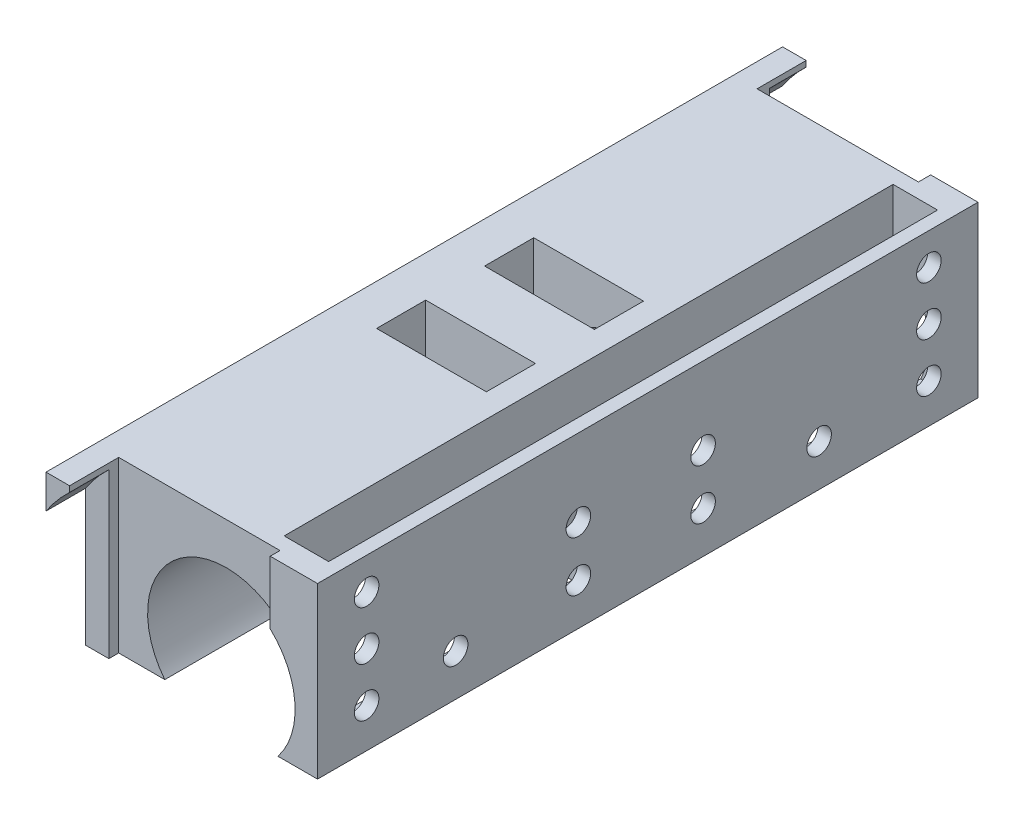
SolidWorks part; units mm, degrees
ref_plane "Plan de face" through (0, 0, 0) normal (0, 0, 1) x (1, 0, 0)
ref_plane "Plan de dessus" through (0, 0, 0) normal (0, 1, 0) x (1, 0, 0)
ref_plane "Plan de droite" through (0, 0, 0) normal (1, 0, 0) x (0, 0, -1)
sketch "Cube" plane through (0, 0, 0) normal (0, 1, 0) x (1, 0, 0)
  line L1 (-109.2105, 63.4868) -> (40.7895, 63.4868)
  line L2 (-109.2105, 63.4868) -> (-109.2105, -86.5132)
  line L3 (-109.2105, -86.5132) -> (40.7895, -86.5132)
  line L4 (40.7895, 63.4868) -> (40.7895, -86.5132)
  dimension "D1" = 150
  dimension "D2" = 150
extrude "Boss.-Extru.1" add sketch "Cube" along normal blind 34.5
sketch "Pave" plane through (0, 34.5, 0) normal (0, 1, 0) x (1, 0, 0)
  line L0 (40.7895, -86.5132) -> (40.7895, 63.4868) construction
  line L1 (-109.2105, -86.5132) -> (40.7895, -86.5132) construction
  line L2 (40.7895, 63.4868) -> (-109.2105, 63.4868) construction
  line L4 (37.7895, -83.5132) -> (-58.2105, -83.5132)
  line L5 (37.7895, -83.5132) -> (37.7895, 60.4868)
  line L6 (37.7895, 60.4868) -> (-58.2105, 60.4868)
  line L7 (-58.2105, -83.5132) -> (-58.2105, 60.4868)
  point P0 (37.7895, -83.5132)
  point P5 (-58.2105, 60.4868)
  dimension "D1" = 3
  dimension "D2" = 3
  dimension "D3" = 3
  dimension "D4" = 99
extrude "Enlèv. mat.-Extru.1" cut sketch "Pave" against normal blind 31.5
sketch "Vis1" plane through (0, 0, 86.5132) normal (0, 0, 1) x (1, 0, 0)
  line L0 (40.7895, 34.5) -> (40.7895, 0) construction
  line L1 (-109.2105, 0) -> (40.7895, 0) construction
  circle A0 centre (33.7895, 10) radius 2.5
  circle A1 centre (33.7895, 20) radius 2.5
  circle A2 centre (33.7895, 30) radius 2.5
  point P0 (33.7895, 10)
  point P3 (33.7895, 20)
  point P4 (33.7895, 30)
  dimension "D1" = 7
  dimension "D2" = 7
  dimension "D3" = 7
  dimension "D4" = 10
  dimension "D5" = 20
  dimension "D6" = 30
extrude "Enlèv. mat.-Extru.2" cut sketch "Vis1" against normal blind 5
sketch "Vis2" plane through (0, 0, -63.4868) normal (0, 0, -1) x (-1, 0, 0)
  line L0 (-40.7895, 34.5) -> (-40.7895, 0) construction
  line L1 (-40.7895, 0) -> (109.2105, 0) construction
  circle A0 centre (-33.7895, 10) radius 2.5
  circle A1 centre (-33.7895, 20) radius 2.5
  circle A2 centre (-33.7895, 30) radius 2.5
  point P0 (-33.7895, 10)
  point P1 (-33.7895, 20)
  point P2 (-33.7895, 30)
  dimension "D1" = 7
  dimension "D2" = 7
  dimension "D3" = 7
  dimension "D4" = 10
  dimension "D5" = 20
  dimension "D6" = 30
extrude "Enlèv. mat.-Extru.3" cut sketch "Vis2" against normal blind 5
sketch "Pave proche moteur" plane through (0, 34.5, 0) normal (0, 1, 0) x (1, 0, 0)
  line L0 (-109.2105, -86.5132) -> (40.7895, -86.5132) construction
  line L1 (-58.2105, 60.4868) -> (-58.2105, -83.5132) construction
  line L2 (40.7895, 63.4868) -> (-109.2105, 63.4868) construction
  line L4 (-61.2105, 50.4868) -> (-73.7105, 50.4868)
  line L5 (-61.2105, 50.4868) -> (-61.2105, -73.5132)
  line L6 (-61.2105, -73.5132) -> (-73.7105, -73.5132)
  line L7 (-73.7105, 50.4868) -> (-73.7105, -73.5132)
  point P0 (-61.2105, -73.5132)
  point P5 (-61.2105, 50.4868)
  dimension "D1" = 13
  dimension "D2" = 3
  dimension "D3" = 13
  dimension "D4" = 3
  dimension "D5" = 12.5
extrude "Enlèv. mat.-Extru.4" cut sketch "Pave proche moteur" against normal blind 31.5
sketch "Pave Roue libre" plane through (0, 34.5, 0) normal (0, 1, 0) x (1, 0, 0)
  line L0 (40.7895, 63.4868) -> (-109.2105, 63.4868) construction
  line L1 (-58.2105, 60.4868) -> (-58.2105, -83.5132) construction
  line L2 (-109.2105, -86.5132) -> (40.7895, -86.5132) construction
  line L3 (-71.5505, 53.4868) -> (-104.4105, 53.4868)
  line L4 (-71.5505, 53.4868) -> (-71.5505, 69.1835)
  line L5 (-71.5505, 69.1835) -> (-104.4105, 69.1835)
  line L6 (-104.4105, 53.4868) -> (-104.4105, 69.1835)
  line L8 (-71.5505, -76.5132) -> (-104.4105, -76.5132)
  line L9 (-71.5505, -76.5132) -> (-71.5505, -94.9327)
  line L10 (-71.5505, -94.9327) -> (-104.4105, -94.9327)
  line L11 (-104.4105, -76.5132) -> (-104.4105, -94.9327)
  point P0 (-71.5505, 53.4868)
  point P9 (-71.5505, -76.5132)
  dimension "D1" = 10
  dimension "D2" = 13.34
  dimension "D3" = 32.86
  dimension "D4" = 13.34
  dimension "D5" = 10
extrude "Enlèv. mat.-Extru.5" cut sketch "Pave Roue libre" against normal blind 36
sketch "Cables" plane through (0, 34.5, 0) normal (0, 1, 0) x (1, 0, 0)
  line L0 (40.7895, 63.4868) -> (-71.5505, 63.4868) construction
  line L1 (-58.2105, 60.4868) -> (-58.2105, -83.5132) construction
  line L2 (-71.5505, -86.5132) -> (40.7895, -86.5132) construction
  line L3 (-58.2105, 60.4868) -> (-58.2105, -83.5132) construction
  line L5 (-100.8905, -5.5132) -> (-78.5305, -5.5132)
  line L6 (-100.8905, -5.5132) -> (-100.8905, 4.4868)
  line L7 (-100.8905, 4.4868) -> (-78.5305, 4.4868)
  line L8 (-78.5305, -5.5132) -> (-78.5305, 4.4868)
  line L9 (-100.8905, -17.5132) -> (-78.5305, -17.5132)
  line L10 (-100.8905, -17.5132) -> (-100.8905, -27.5132)
  line L11 (-100.8905, -27.5132) -> (-78.5305, -27.5132)
  line L12 (-78.5305, -17.5132) -> (-78.5305, -27.5132)
  point P0 (-100.8905, -5.5132)
  point P5 (-100.8905, -17.5132)
  dimension "D1" = 69
  dimension "D2" = 42.68
  dimension "D3" = 69
  dimension "D4" = 42.68
  dimension "D5" = 22.36
  dimension "D6" = 10
  dimension "D7" = 22.36
  dimension "D8" = 10
extrude "Enlèv. mat.-Extru.6" cut sketch "Cables" against normal blind 36
sketch "Roue ext" plane through (0, 0, 86.5132) normal (0, 0, 1) x (1, 0, 0)
  circle A0 centre (-82.5, 10) radius 32
  point P0 (-82.5, 10)
extrude "Enlèv. mat.-Extru.7" cut sketch "Roue ext" against normal blind 8
sketch "Roue inter" plane through (0, 0, 86.5132) normal (0, 0, 1) x (1, 0, 0)
  circle A0 centre (-82.5, 10) radius 16.02
  point P0 (-82.5, 10)
extrude "Enlèv. mat.-Extru.8" cut sketch "Roue inter" against normal blind 69
sketch "Roue ext2" plane through (0, 0, -63.4868) normal (0, 0, -1) x (-1, 0, 0)
  circle A0 centre (82.5, 10) radius 32
  point P0 (82.5, 10)
extrude "Enlèv. mat.-Extru.9" cut sketch "Roue ext2" against normal blind 7.5
sketch "Roue inter2" plane through (0, 0, -63.4868) normal (0, 0, -1) x (-1, 0, 0)
  circle A0 centre (82.5, 10) radius 16.02
  point P0 (82.5, 10)
extrude "Enlèv. mat.-Extru.10" cut sketch "Roue inter2" against normal blind 69
sketch "Vis Moteur pour support" plane through (-58.2105, 0, 0) normal (1, 0, 0) x (0, 0, -1)
  line L0 (55.9868, 3) -> (-78.5132, 3) construction
  line L1 (-78.5132, 3) -> (-78.5132, 30.8332) construction
  line L2 (55.9868, 30.8332) -> (55.9868, 3) construction
  circle A0 centre (-68.5132, 8) radius 2.5
  circle A1 centre (-68.5132, 18) radius 2.5
  circle A2 centre (-68.5132, 28) radius 2.5
  circle A3 centre (45.9868, 8) radius 2.5
  circle A4 centre (45.9868, 18) radius 2.5
  circle A5 centre (45.9868, 28) radius 2.5
  point P0 (-68.5132, 8)
  point P1 (-68.5132, 18)
  point P2 (-68.5132, 28)
  point P13 (45.9868, 18)
  point P14 (45.9868, 28)
  point P15 (45.9868, 8)
  dimension "D7" = 5
  dimension "D1" = 5
  dimension "D2" = 15
  dimension "D3" = 25
  dimension "D4" = 10
  dimension "D5" = 10
  dimension "D6" = 10
  dimension "D8" = 15
  dimension "D9" = 25
  dimension "D10" = 10
  dimension "D11" = 10
  dimension "D12" = 10
extrude "Enlèv. mat.-Extru.11" cut sketch "Vis Moteur pour support" against normal blind 10
sketch "Esquisse1" plane through (0, 3, 0) normal (0, 1, 0) x (1, 0, 0)
  line L0 (-58.2105, 55.9868) -> (-58.2105, -78.5132) construction
  line L1 (37.7895, 60.4868) -> (-51.275, 60.4868) construction
  line L2 (37.7895, -83.5132) -> (37.7895, 60.4868) construction
  line L3 (-58.2105, -15.5132) -> (-14.2105, -15.5132)
  line L4 (-58.2105, -15.5132) -> (-58.2105, -7.5132)
  line L5 (-58.2105, -7.5132) -> (-14.2105, -7.5132)
  line L6 (37.7895, -15.5132) -> (37.7895, -7.5132)
  line L7 (-51.275, -83.5132) -> (37.7895, -83.5132) construction
  line L8 (-14.2105, 60.4868) -> (-6.2105, 60.4868)
  line L9 (-14.2105, 60.4868) -> (-14.2105, -7.5132)
  line L10 (-14.2105, -83.5132) -> (-6.2105, -83.5132)
  line L11 (-6.2105, 60.4868) -> (-6.2105, -7.5132)
  line L12 (-14.2105, -15.5132) -> (-14.2105, -83.5132)
  line L13 (-6.2105, -15.5132) -> (37.7895, -15.5132)
  line L14 (-6.2105, -15.5132) -> (-6.2105, -83.5132)
  line L15 (-6.2105, -7.5132) -> (37.7895, -7.5132)
  point P0 (-58.2105, -11.5132)
  point P5 (-58.2105, -7.5132)
  point P6 (-58.2105, -15.5132)
  point P13 (-10.2105, 60.4868)
  point P14 (-14.2105, 60.4868)
  point P15 (-6.2105, 60.4868)
  dimension "D1" = 72
  dimension "D2" = 68
  dimension "D3" = 76
  dimension "D4" = 48
  dimension "D5" = 52
  dimension "D6" = 44
extrude "Boss.-Extru.2" add sketch "Esquisse1" along normal blind 10
sketch "Esquisse2" plane through (0, 0, 15.5132) normal (0, 0, 1) x (1, 0, 0)
  line L0 (-58.2105, 3) -> (-14.2105, 3) construction
  line L1 (-6.2105, 3) -> (37.7895, 3) construction
  circle A0 centre (-43.9429, 8) radius 2.5
  circle A1 centre (-26.8896, 8) radius 2.5
  circle A2 centre (9.5885, 8) radius 2.5
  circle A3 centre (23.5624, 8) radius 2.5
  point P0 (-43.9429, 8)
  point P1 (-26.8896, 8)
  point P4 (9.5885, 8)
  point P5 (23.5624, 8)
  dimension "D1" = 5
  dimension "D2" = 5
  dimension "D3" = 5
extrude "Enlèv. mat.-Extru.12" cut sketch "Esquisse2" against normal blind 10
sketch "Esquisse3" plane through (0, 3, 0) normal (0, 1, 0) x (1, 0, 0)
  line L0 (-68.0903, -73.5132) -> (-61.2105, -73.5132) construction
  line L1 (-61.2105, 50.4868) -> (-64.6504, 50.4868)
  line L2 (-61.2105, 50.4868) -> (-61.2105, -73.5132)
  line L3 (-61.2105, -73.5132) -> (-64.6504, -73.5132)
  line L4 (-64.6504, 50.4868) -> (-64.6504, -73.5132)
extrude "Boss.-Extru.3" add sketch "Esquisse3" along normal blind 31
sketch "Esquisse5" plane through (0, 34, 0) normal (0, 1, 0) x (1, 0, 0)
  line L1 (-61.2105, 50.4868) -> (-64.6504, 50.4868)
  line L2 (-61.2105, 50.4868) -> (-61.2105, -73.5132)
  line L3 (-61.2105, -73.5132) -> (-64.6504, -73.5132)
  line L4 (-64.6504, 50.4868) -> (-64.6504, -73.5132)
extrude "Boss.-Extru.4" add sketch "Esquisse5" along normal blind 0.5
sketch "Esquisse6" plane through (-58.2105, 0, 0) normal (1, 0, 0) x (0, 0, -1)
  circle A0 centre (-68.5132, 28) radius 2.5
  circle A1 centre (-68.5132, 18) radius 2.5
  circle A2 centre (-68.5132, 8) radius 2.5
  circle A3 centre (45.9868, 28) radius 2.5
  circle A4 centre (45.9868, 18) radius 2.5
  circle A5 centre (45.9868, 8) radius 2.5
extrude "Enlèv. mat.-Extru.13" cut sketch "Esquisse6" against normal blind 10
sketch "Esquisse7" plane through (-58.2105, 0, 0) normal (1, 0, 0) x (0, 0, -1)
  circle A0 centre (0, 8.5279) radius 2.5
  circle A2 centre (0, 18.7509) radius 2.5
  circle A3 centre (-25.4002, 8.5279) radius 2.5
  circle A4 centre (-25.4002, 18.7509) radius 2.5
  circle A5 centre (-50.3865, 8.5279) radius 2.5
  circle A6 centre (23.6295, 8.5279) radius 2.5
extrude "Enlèv. mat.-Extru.14" cut sketch "Esquisse7" against normal blind 10
sketch "Esquisse8" plane through (0, 3, 0) normal (0, 1, 0) x (1, 0, 0)
  line L0 (37.7895, -83.5132) -> (37.7895, -15.5132) construction
  line L1 (-58.2105, -83.5132) -> (37.7895, -83.5132) construction
  line L2 (37.7895, 60.4868) -> (-6.2105, 60.4868) construction
  circle A0 centre (19.7895, -43.5132) radius 2.5
  circle A1 centre (19.7895, 20.4868) radius 2.5
  point P0 (19.7895, -43.5132)
  point P7 (19.7895, 20.4868)
  dimension "D3" = 40
  dimension "D1" = 18
  dimension "D2" = 40
extrude "Enlèv. mat.-Extru.15" cut sketch "Esquisse8" against normal blind 10
sketch "Esquisse10" plane through (0, 34.5, 0) normal (0, 1, 0) x (1, 0, 0)
  line L1 (-61.9148, -86.5132) -> (40.7895, -86.5132)
  line L2 (-61.9148, -86.5132) -> (-61.9148, 63.4868)
  line L3 (-61.9148, 63.4868) -> (40.7895, 63.4868)
  line L4 (40.7895, -86.5132) -> (40.7895, 63.4868)
extrude "Enlèv. mat.-Extru.16" cut sketch "Esquisse10" against normal blind 40
